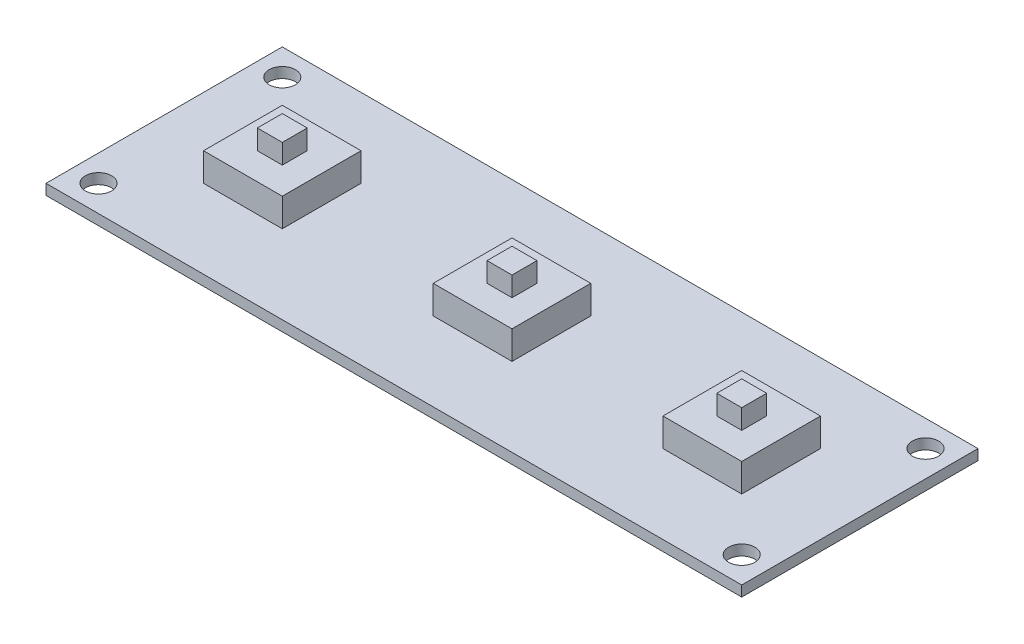
SolidWorks part; units mm, degrees
ref_plane "Front Plane" through (0, 0, 0) normal (0, 0, 1) x (1, 0, 0)
ref_plane "Top Plane" through (0, 0, 0) normal (0, 1, 0) x (1, 0, 0)
ref_plane "Right Plane" through (0, 0, 0) normal (1, 0, 0) x (0, 0, -1)
sketch "Sketch1" plane through (0, 0, 0) normal (0, 1, 0) x (1, 0, 0)
  line L1 (0, 0) -> (12, 0)
  line L2 (0, 0) -> (0, 12)
  line L3 (0, 12) -> (12, 12)
  line L4 (12, 0) -> (12, 12)
  dimension "D1" = 12
  dimension "D2" = 12
extrude "Boss-Extrude1" add sketch "Sketch1" along normal blind 4.3
sketch "Sketch2" plane through (0, 4.3, 0) normal (0, 1, 0) x (1, 0, 0)
  line L1 (4.1, 7.9) -> (7.9, 7.9)
  line L2 (4.1, 7.9) -> (4.1, 4.1)
  line L3 (4.1, 4.1) -> (7.9, 4.1)
  line L4 (7.9, 7.9) -> (7.9, 4.1)
  line L5 (0, 12) -> (0, 0) construction
  line L6 (12, 12) -> (0, 12) construction
  circle A0 centre (6, 6) radius 2.687
  point P6 (0, 0)
  point P7 (0, 0)
  dimension "D1" = 3.8
  dimension "D2" = 3.8
  dimension "D3" = 6
  dimension "D4" = 6
extrude "Boss-Extrude2" add sketch "Sketch2" along normal blind 3 contours L4 L1 L2 L3
sketch "Sketch3" plane through (0, 0, 0) normal (0, -1, 0) x (1, 0, 0)
  line L0 (0, -12) -> (0, 0) construction
  line L1 (-12, 12) -> (94, 12)
  line L2 (-12, 12) -> (-12, -24)
  line L3 (-12, -24) -> (94, -24)
  line L4 (94, 12) -> (94, -24)
  line L5 (0, 0) -> (12, 0) construction
  line L6 (12, -12) -> (0, -12) construction
  circle A0 centre (-8, -20) radius 2
  circle A1 centre (-8, 8) radius 2
  circle A2 centre (90, 8) radius 2
  circle A3 centre (90, -20) radius 2
  point P18 (0, 0)
  point P20 (90.1873, -20.709)
  dimension "D5" = 4
  dimension "D8" = 4
  dimension "D13" = 4
  dimension "D14" = 4
  dimension "D1" = 12
  dimension "D2" = 12
  dimension "D3" = 12
  dimension "D4" = 106
  dimension "D6" = 4
  dimension "D7" = 4
  dimension "D9" = 4
  dimension "D10" = 4
  dimension "D11" = 4
  dimension "D12" = 4
  dimension "D15" = 4
  dimension "D16" = 4
extrude "Boss-Extrude3" add sketch "Sketch3" along normal blind 1.6
sketch "Sketch4" plane through (0, 0, 0) normal (0, 1, 0) x (1, 0, 0)
  line L1 (35, 12) -> (47, 12)
  line L2 (35, 12) -> (35, 0)
  line L3 (35, 0) -> (47, 0)
  line L4 (47, 12) -> (47, 0)
  line L5 (0, 12) -> (0, 0) construction
  line L6 (12, 12) -> (0, 12) construction
  line L7 (70, 12) -> (82, 12)
  line L8 (70, 12) -> (70, 0)
  line L9 (70, 0) -> (82, 0)
  line L10 (82, 12) -> (82, 0)
  line L11 (12, 12) -> (0, 12) construction
  dimension "D1" = 35
  dimension "D2" = 35
  dimension "D3" = 12
  dimension "D4" = 12
  dimension "D5" = 12
  dimension "D6" = 12
  dimension "D7" = 0
  dimension "D8" = 0
extrude "Boss-Extrude4" add sketch "Sketch4" along normal blind 4.3
sketch "Sketch5" plane through (0, 4.3, 0) normal (0, 1, 0) x (1, 0, 0)
  line L1 (39.1, 7.9) -> (42.9, 7.9)
  line L2 (39.1, 7.9) -> (39.1, 4.1)
  line L3 (39.1, 4.1) -> (42.9, 4.1)
  line L4 (42.9, 7.9) -> (42.9, 4.1)
  line L5 (74.1, 7.9) -> (77.9, 7.9)
  line L6 (74.1, 7.9) -> (74.1, 4.1)
  line L7 (74.1, 4.1) -> (77.9, 4.1)
  line L8 (77.9, 7.9) -> (77.9, 4.1)
  line L9 (35, 12) -> (35, 0) construction
  line L10 (47, 12) -> (35, 12) construction
  line L11 (82, 12) -> (70, 12) construction
  line L12 (70, 12) -> (70, 0) construction
  dimension "D1" = 3.8
  dimension "D2" = 4.1
  dimension "D3" = 4.1
  dimension "D4" = 3.8
  dimension "D5" = 3.8
  dimension "D6" = 4.1
  dimension "D7" = 4.1
extrude "Boss-Extrude5" add sketch "Sketch5" along normal blind 3 contours L2 L1 L4 L3 | L6 L5 L8 L7
